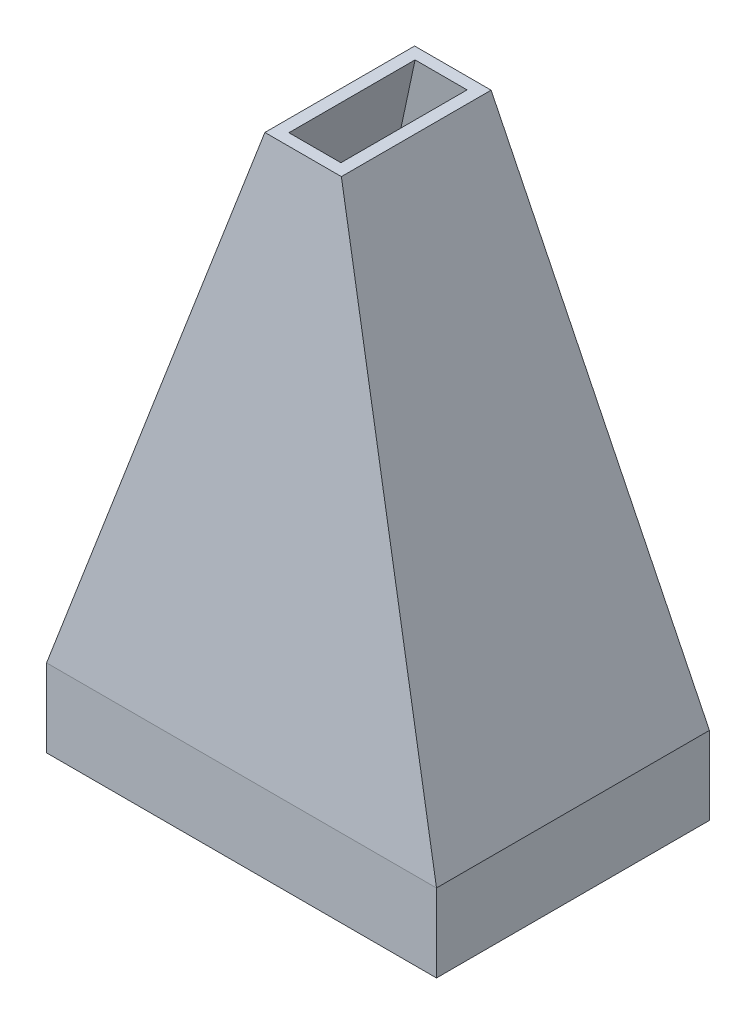
SolidWorks part; units mm, degrees
ref_plane "Front Plane" through (0, 0, 0) normal (0, 0, 1) x (1, 0, 0)
ref_plane "Top Plane" through (0, 0, 0) normal (0, 1, 0) x (1, 0, 0)
ref_plane "Right Plane" through (0, 0, 0) normal (1, 0, 0) x (0, 0, -1)
sketch "Sketch2" plane through (0, 0, 0) normal (0, 1, 0) x (1, 0, 0)
  line L1 (-50, -35) -> (50, -35)
  line L2 (-50, -35) -> (-50, 35)
  line L3 (-50, 35) -> (50, 35)
  line L4 (50, -35) -> (50, 35)
  line L5 (0, 35) -> (0, -35) construction
  line L6 (-50, 0) -> (50, 0) construction
  point P0 (0, 0)
  dimension "D1" = 100
  dimension "D2" = 70
extrude "Boss-Extrude1" add sketch "Sketch2" along normal blind 150
sketch "Sketch3" plane through (-50, 0, 0) normal (-1, 0, 0) x (0, 0, 1)
  line L0 (-19.2, 150) -> (-19.2, 0) construction
  line L1 (-35, 150) -> (35, 150) construction
  line L2 (-35, 0) -> (35, 0) construction
  line L3 (19.2, 150) -> (19.2, 0) construction
  line L4 (0, 150) -> (0, 0) construction
  line L5 (19.2, 75) -> (-19.2, 75) construction
  line L6 (-35, 150) -> (-35, 0) construction
  line L7 (-6.5, 35.02) -> (6.5, 35.02) construction
  line L8 (-6.5, 35.02) -> (-6.5, 89.02) construction
  line L9 (-6.5, 89.02) -> (6.5, 89.02) construction
  line L10 (6.5, 35.02) -> (6.5, 89.02) construction
  line L11 (0, 89.02) -> (0, 35.02) construction
  line L12 (-6.5, 62.02) -> (6.5, 62.02) construction
  line L13 (35, 150) -> (35, 0) construction
  line L14 (-35, 20) -> (-19.2, 150)
  line L15 (19.2, 150) -> (35, 20)
  line L16 (35, 20) -> (35, 150)
  line L17 (35, 150) -> (19.2, 150)
  line L18 (-19.2, 150) -> (-35, 150)
  line L19 (-35, 150) -> (-35, 20)
  point P11 (0, 140)
  point P14 (0, 75)
  point P15 (0, 62.02)
  point P16 (0, 75)
  point P17 (0, 92.8)
  point P18 (0, 62.02)
  point P22 (0, 102.43)
  point P23 (-35, 0)
  point P24 (-35, 20)
  point P25 (35, 20)
  point P28 (35, 0)
  dimension "D1" = 38.4
  dimension "D2" = 30.78
  dimension "D3" = 47.2
  dimension "D4" = 10
  dimension "D5" = 54
  dimension "D6" = 13
  dimension "D7" = 9.63
  dimension "D8" = 20
  dimension "D9" = 20
extrude "Cut-Extrude1" cut sketch "Sketch3" against normal through all
sketch "Sketch4" plane through (0, 0, 0) normal (0, 0, 1) x (1, 0, 0)
  line L0 (0, 150) -> (0, 0) construction
  line L1 (50, 150) -> (-50, 150) construction
  line L2 (-12.9, 140) -> (12.9, 140) construction
  line L3 (-140, 35.02) -> (140, 35.02) construction
  line L4 (-140, 35.02) -> (-140, 89.02) construction
  line L5 (-140, 89.02) -> (140, 89.02) construction
  line L6 (140, 35.02) -> (140, 89.02) construction
  line L7 (0, 89.02) -> (0, 35.02) construction
  line L8 (-140, 62.02) -> (140, 62.02) construction
  line L9 (-5, 65.8) -> (5, 65.8) construction
  line L10 (-5, 65.8) -> (-5, 119.8) construction
  line L11 (-5, 119.8) -> (5, 119.8) construction
  line L12 (5, 65.8) -> (5, 119.8) construction
  line L13 (0, 119.8) -> (0, 65.8) construction
  line L14 (-5, 92.8) -> (5, 92.8) construction
  line L15 (-50, 20) -> (-9.8083, 150)
  line L16 (50, 20) -> (9.8083, 150)
  line L17 (-9.8083, 150) -> (-50, 150)
  line L18 (-50, 150) -> (-50, 20)
  line L19 (9.8083, 150) -> (50, 150)
  line L20 (50, 150) -> (50, 20)
  point P5 (0, 140)
  point P6 (0, 92.8)
  point P7 (0, 62.02)
  point P8 (0, 62.02)
  point P12 (0, 92.8)
  point P19 (0, 140)
  dimension "D1" = 10
  dimension "D2" = 47.2
  dimension "D3" = 30.78
  dimension "D4" = 54
  dimension "D5" = 280
  dimension "D6" = 54
  dimension "D7" = 10
  dimension "D8" = 25.8
extrude "Cut-Extrude2" cut sketch "Sketch4" against normal through all both and the other way through all
shell "Shell1" thickness 3
